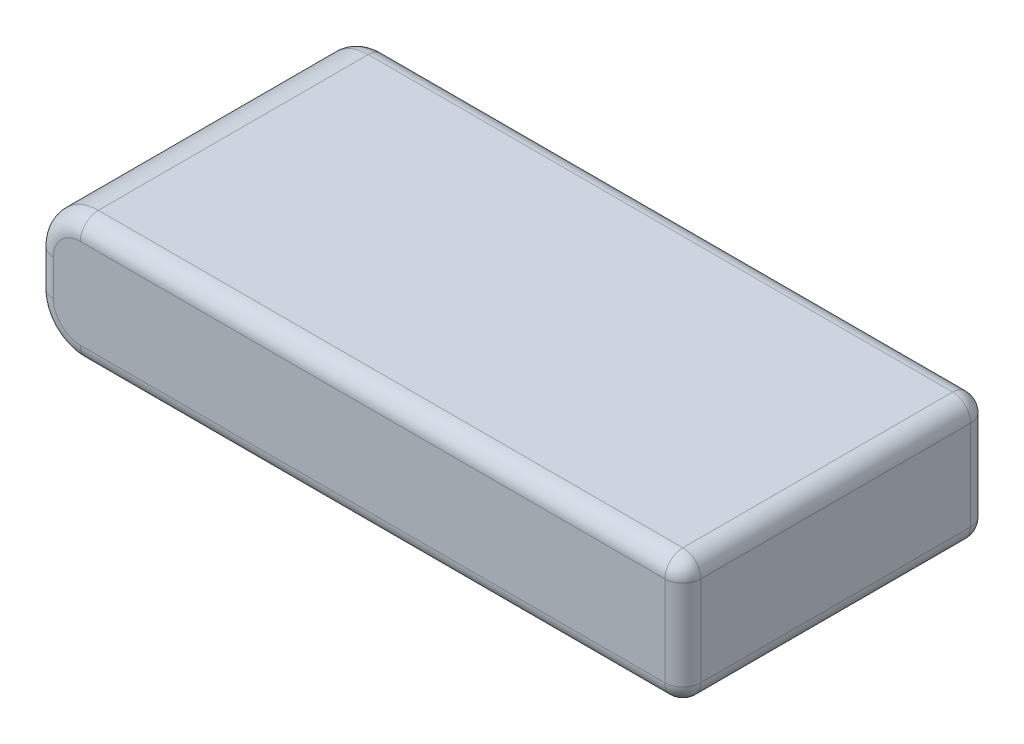
SolidWorks part; units mm, degrees
ref_plane "Front Plane" through (0, 0, 0) normal (0, 0, 1) x (1, 0, 0)
ref_plane "Top Plane" through (0, 0, 0) normal (0, 1, 0) x (1, 0, 0)
ref_plane "Right Plane" through (0, 0, 0) normal (1, 0, 0) x (0, 0, -1)
sketch "Sketch2" plane through (0, 0, 0) normal (0, 1, 0) x (1, 0, 0)
  line L1 (-36, -17) -> (36, -17)
  line L2 (-36, -17) -> (-36, 17)
  line L3 (-36, 17) -> (36, 17)
  line L4 (36, -17) -> (36, 17)
  line L5 (-36, -17) -> (36, 17) construction
  line L6 (-36, 17) -> (36, -17) construction
  point P0 (0, 0)
  dimension "D1" = 34
  dimension "D2" = 72
extrude "Boss-Extrude1" add sketch "Sketch2" along normal blind 14
fillet "Fillet5" radius 5 2 edges at (-36, 0, 0) (-36, 14, 0)
fillet "Fillet6" radius 2 14 edges at (-34.5355, 12.5355, -17) (-34.5355, 1.4645, -17) (-34.5355, 1.4645, 17) (-34.5355, 12.5355, 17) (36, 7, 17) (36, 14, 0) (36, 7, -17) (36, 0, 0) (2.5, 14, -17) (2.5, 0, -17) (2.5, 0, 17) (2.5, 14, 17) (-36, 7, -17) (-36, 7, 17)
